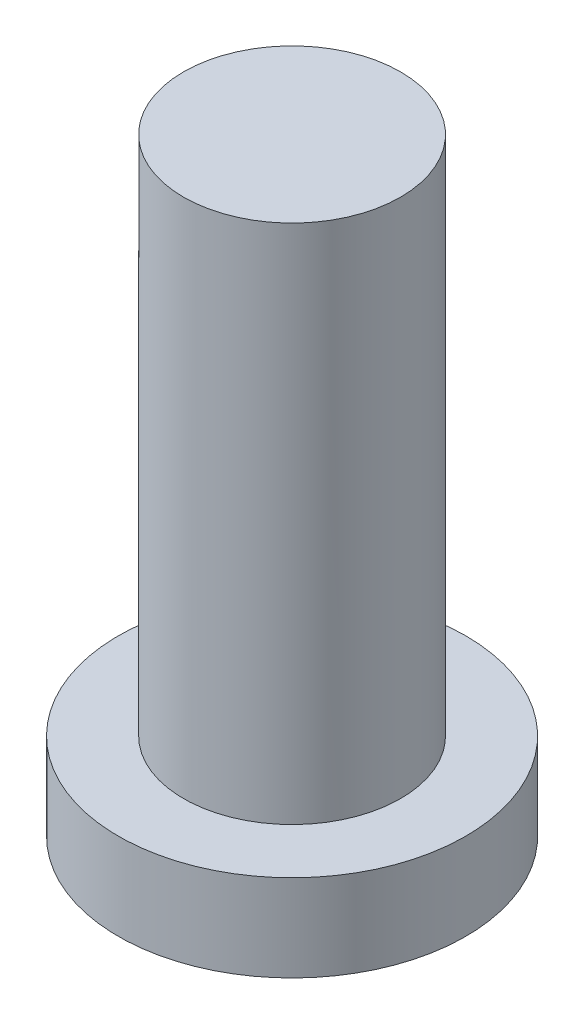
SolidWorks part; units mm, degrees
ref_plane "Front Plane" through (0, 0, 0) normal (0, 0, 1) x (1, 0, 0)
ref_plane "Top Plane" through (0, 0, 0) normal (0, 1, 0) x (1, 0, 0)
ref_plane "Right Plane" through (0, 0, 0) normal (1, 0, 0) x (0, 0, -1)
sketch "Sketch1" plane through (0, 0, 0) normal (0, 1, 0) x (1, 0, 0)
  circle A0 centre (0, 0) radius 1.25
extrude "Boss-Extrude1" add sketch "Sketch1" along normal blind 6
sketch "Sketch2" plane through (0, 0, 0) normal (0, -1, 0) x (1, 0, 0)
  circle A0 centre (0, 0) radius 2
extrude "Boss-Extrude2" add sketch "Sketch2" along normal blind 1
